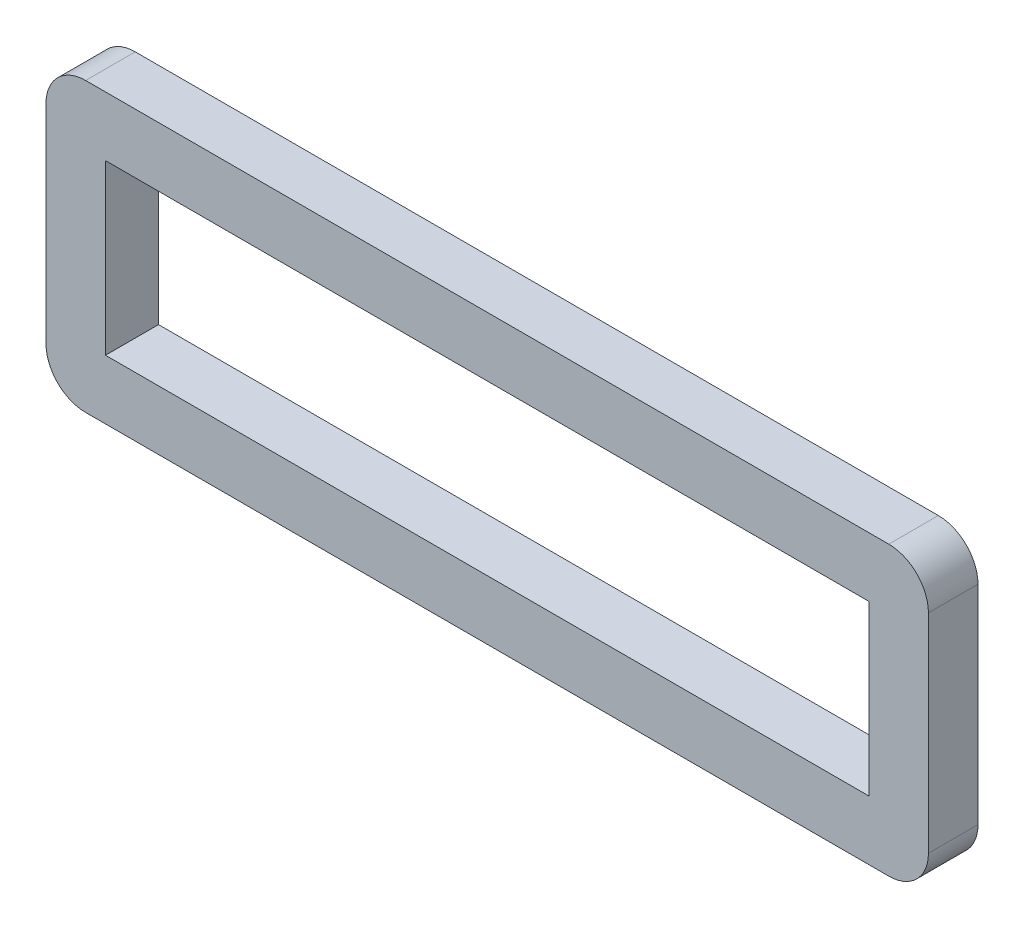
SolidWorks part; units mm, degrees
ref_plane "Front Plane" through (0, 0, 0) normal (0, 0, 1) x (1, 0, 0)
ref_plane "Top Plane" through (0, 0, 0) normal (0, 1, 0) x (1, 0, 0)
ref_plane "Right Plane" through (0, 0, 0) normal (1, 0, 0) x (0, 0, -1)
sketch "Sketch1" plane through (0, 0, 0) normal (0, 0, 1) x (1, 0, 0)
  line L1 (-38.5, 8.5) -> (38.5, 8.5)
  line L2 (-38.5, 8.5) -> (-38.5, -8.5)
  line L3 (-38.5, -8.5) -> (38.5, -8.5)
  line L4 (38.5, 8.5) -> (38.5, -8.5)
  line L5 (-38.5, 8.5) -> (38.5, -8.5) construction
  line L6 (-38.5, -8.5) -> (38.5, 8.5) construction
  line L7 (-44.5, 14.5) -> (44.5, 14.5)
  line L8 (-44.5, 14.5) -> (-44.5, -14.5)
  line L9 (-44.5, -14.5) -> (44.5, -14.5)
  line L10 (44.5, 14.5) -> (44.5, -14.5)
  line L11 (-44.5, 14.5) -> (44.5, -14.5) construction
  line L12 (-44.5, -14.5) -> (44.5, 14.5) construction
  point P0 (0, 0)
  point P5 (0, 0)
  dimension "D1" = 17
  dimension "D2" = 77
  dimension "D3" = 6
  dimension "D4" = 6
extrude "Boss-Extrude1" add sketch "Sketch1" along normal blind 5
fillet "Fillet1" radius 4 4 edges at (44.5, -14.5, 2.5) (44.5, 14.5, 2.5) (-44.5, -14.5, 2.5) (-44.5, 14.5, 2.5)
draft "Draft1" type of draft neutral plane draft angle 4 faces to draft 4 face at (38.5, 0, 2.5) face at (0, -8.5, 2.5) face at (-38.5, 0, 2.5) face at (0, 8.5, 2.5) neutral plane through (0, 0, 5) neutral plane normal (0, 0, 1) parameters "D1"=4
